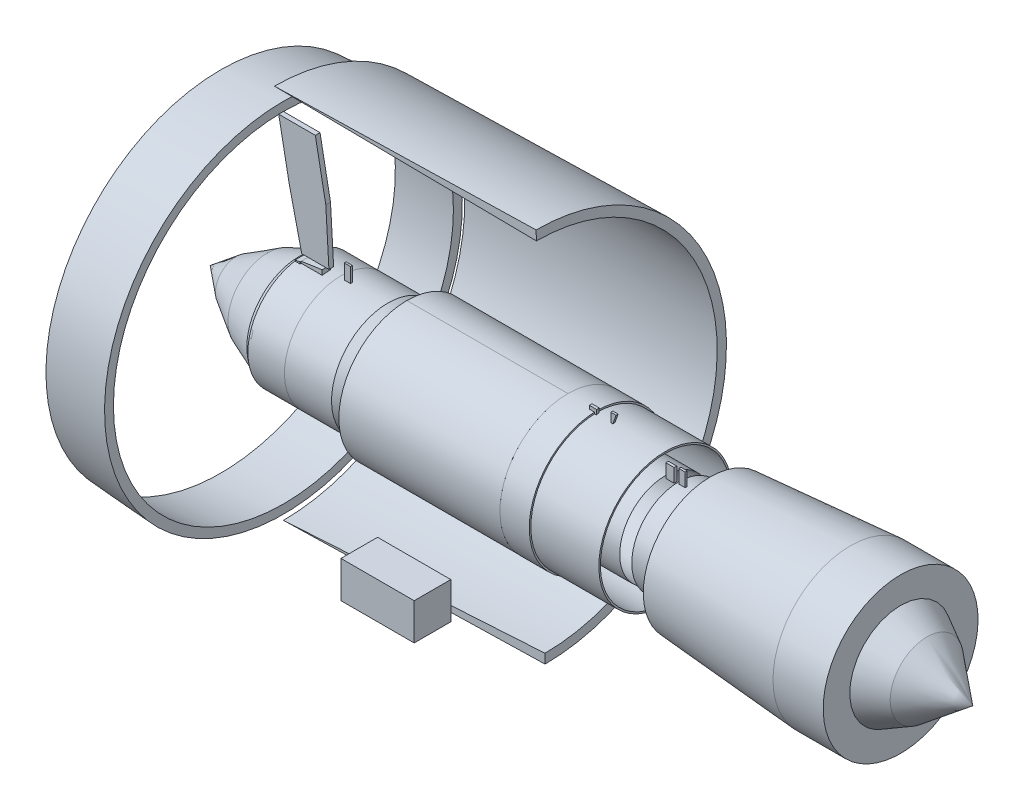
SolidWorks part; units mm, degrees
ref_plane "Front Plane" through (0, 0, 0) normal (0, 0, 1) x (1, 0, 0)
ref_plane "Top Plane" through (0, 0, 0) normal (0, 1, 0) x (1, 0, 0)
ref_plane "Right Plane" through (0, 0, 0) normal (1, 0, 0) x (0, 0, -1)
sketch "Sketch1" plane through (0, 0, 0) normal (0, 0, 1) x (1, 0, 0)
  line L0 (0, 0) -> (1200, 0) construction
  line L1 (0, 0) -> (250, 200)
  line L2 (250, 200) -> (550, 380)
  line L3 (550, 380) -> (850, 500)
  line L4 (850, 500) -> (900, 540)
  line L5 (900, 540) -> (920, 540)
  line L6 (920, 540) -> (920, 460)
  line L7 (920, 460) -> (850, 460)
  line L8 (850, 460) -> (550, 350)
  line L9 (550, 350) -> (250, 170)
  line L10 (250, 170) -> (50, 0)
  line L11 (50, 0) -> (0, 0)
revolve "Revolve1" add sketch "Sketch1" angle 360 about L0
sketch "Sketch2" plane through (0, 0, 0) normal (0, 0, 1) x (1, 0, 0)
  line L0 (0, 0) -> (2000, 0) construction
  line L1 (900, 220) -> (900, 540)
  line L2 (900, 540) -> (900, -540) construction
  line L3 (900, 540) -> (1250, 540)
  line L4 (1250, 540) -> (1250, 220)
  line L5 (1250, 220) -> (900, 220)
revolve "Revolve2" add sketch "Sketch2" angle 360 about L0
sketch "Sketch3" plane through (0, 0, 0) normal (0, 0, 1) x (1, 0, 0)
  line L0 (950, 500) -> (950, 550)
  line L1 (950, 550) -> (1150, 580)
  line L2 (1150, 580) -> (1150, 500)
  line L3 (1150, 500) -> (950, 500)
extrude "Boss-Extrude1" add sketch "Sketch3" along normal blind 80 separate body
sketch "Sketch4" plane through (0, 0, 0) normal (0, 0, 1) x (1, 0, 0)
  line L0 (920, 580) -> (800, 1100)
  line L1 (800, 1100) -> (700, 1625)
  line L2 (700, 1625) -> (1050, 1625)
  line L3 (1050, 1625) -> (1150, 1100)
  line L4 (1150, 1100) -> (1180, 580)
  line L5 (1180, 580) -> (920, 580)
extrude "Boss-Extrude2" add sketch "Sketch4" along normal blind 45 separate body
sketch "Sketch5" plane through (0, 0, 0) normal (0, 0, 1) x (1, 0, 0)
  line L0 (900, 490) -> (900, 540)
  line L1 (900, 540) -> (900, -540) construction
  line L2 (900, 540) -> (950, 550)
  line L3 (950, 550) -> (950, 490)
  line L4 (950, 490) -> (900, 490)
extrude "Boss-Extrude3" add sketch "Sketch5" along normal blind 90 separate body
sketch "Sketch6" plane through (0, 0, 0) normal (0, 0, 1) x (1, 0, 0)
  line L0 (0, 0) -> (2000, 0) construction
  line L1 (100, 1670) -> (700, 1710)
  line L2 (700, 1710) -> (700, 1625)
  line L3 (700, 1625) -> (100, 1670)
revolve "Revolve3" add sketch "Sketch6" angle 360 about L0
sketch "Sketch7" plane through (0, 0, 0) normal (0, 0, 1) x (1, 0, 0)
  line L0 (0, 0) -> (3000, 0) construction
  line L1 (700, 1630) -> (700, 1710)
  line L2 (700, -1710) -> (700, 1710) construction
  line L3 (700, 1710) -> (750, 1750)
  line L4 (750, 1750) -> (700, 1710)
  line L5 (700, 1710) -> (2150, 1710)
  line L6 (2150, 1710) -> (2150, 1750)
  line L7 (2150, 1750) -> (2200, 1750)
  line L8 (2200, 1750) -> (2200, 1630)
  line L9 (2200, 1630) -> (700, 1630)
sketch "Sketch8" plane through (0, 0, 0) normal (0, 0, 1) x (1, 0, 0)
  line L0 (0, 0) -> (3000, 0) construction
  line L1 (1250, 250) -> (1250, 540)
  line L2 (1250, -540) -> (1250, 540) construction
  line L3 (1250, 540) -> (1400, 540)
  line L4 (1400, 540) -> (1550, 540)
  line L5 (1550, 540) -> (1700, 540)
  line L6 (1700, 540) -> (1850, 470)
  line L7 (1850, 470) -> (1850, 250)
  line L8 (1850, 250) -> (1250, 250)
revolve "Revolve5" add sketch "Sketch8" angle 360 about L0
sketch "Sketch9" plane through (0, 0, 0) normal (0, 0, 1) x (1, 0, 0)
  line L0 (1300, 500) -> (1300, 680)
  line L1 (1300, 680) -> (1360, 680)
  line L2 (1360, 680) -> (1360, 500)
  line L3 (1360, 500) -> (1300, 500)
extrude "Boss-Extrude5" add sketch "Sketch9" along normal blind 18 separate body
sketch "Sketch10" plane through (0, 0, 0) normal (0, 0, 1) x (1, 0, 0)
  line L0 (0, 0) -> (3000, 0) construction
  line L1 (1500, 500) -> (1500, 700)
  line L2 (1500, 700) -> (1500, 500)
  line L3 (1500, 500) -> (1450, 500)
sketch "Sketch11" plane through (0, 0, 0) normal (0, 0, 1) x (1, 0, 0)
  line L0 (0, 0) -> (4000, 0) construction
  line L1 (1900, 280) -> (1900, 460)
  line L2 (1900, 460) -> (3400, 460)
  line L3 (3400, 460) -> (3400, 280)
  line L4 (3400, 280) -> (1900, 280)
revolve "Revolve7" add sketch "Sketch11" angle 360 about L0
sketch "Sketch12" plane through (0, 0, 0) normal (0, 0, 1) x (1, 0, 0)
  line L0 (2000, 450) -> (2000, 580)
  line L1 (2000, 580) -> (2050, 580)
  line L2 (2050, 580) -> (2050, 450)
  line L3 (2050, 450) -> (2000, 450)
extrude "Boss-Extrude6" add sketch "Sketch12" along normal blind 15 separate body
sketch "Sketch13" plane through (0, 0, 0) normal (0, 0, 1) x (1, 0, 0)
  line L0 (0, 0) -> (4000, 0) construction
  line L1 (1880, 580) -> (1880, 650)
  line L2 (1880, 650) -> (3420, 650)
  line L3 (3420, 650) -> (3420, 580)
  line L4 (3420, 580) -> (1880, 580)
revolve "Revolve8" add sketch "Sketch13" angle 180 about L0
sketch "Sketch14" plane through (0, 0, 0) normal (0, 0, 1) x (1, 0, 0)
  line L0 (0, 0) -> (4000, 0) construction
  line L1 (1880, -580) -> (1880, -650)
  line L2 (1880, -650) -> (3420, -650)
  line L3 (3420, -650) -> (3420, 650) construction
  line L4 (3420, -650) -> (3420, -580)
  line L5 (3420, -580) -> (1880, -580)
revolve "Revolve9" add sketch "Sketch14" angle 180 about L0
sketch "Sketch15" plane through (0, 0, 0) normal (0, 0, 1) x (1, 0, 0)
  line L0 (0, 0) -> (5000, 0) construction
  line L1 (3420, 350) -> (3420, 650)
  line L2 (3420, -650) -> (3420, 650) construction
  line L3 (3420, 650) -> (3700, 650)
  line L4 (3700, 650) -> (3700, 350)
  line L5 (3700, 350) -> (3420, 350)
revolve "Revolve10" add sketch "Sketch15" angle 360 about L0
sketch "Sketch16" plane through (0, 0, 0) normal (0, 0, 1) x (1, 0, 0)
  line L0 (0, 0) -> (5000, 0) construction
  line L1 (3700, 620) -> (3700, 635)
  line L2 (3700, 635) -> (4350, 635)
  line L3 (4350, 635) -> (4350, 620)
  line L4 (4350, 620) -> (3700, 620)
revolve "Revolve11" add sketch "Sketch16" angle 360 about L0
sketch "Sketch17" plane through (0, 0, 0) normal (0, 0, 1) x (1, 0, 0)
  line L0 (0, 0) -> (5000, 0) construction
  line L1 (3700, 420) -> (3700, 435)
  line L2 (3700, -650) -> (3700, 650) construction
  line L3 (3700, 435) -> (4350, 435)
  line L4 (4350, -635) -> (4350, 635) construction
  line L5 (4350, 435) -> (3700, 420)
revolve "Revolve12" add sketch "Sketch17" angle 360 about L0
sketch "Sketch18" plane through (0, 0, 0) normal (0, 0, 1) x (1, 0, 0)
  line L0 (3650, 500) -> (3650, 680)
  line L1 (3650, 680) -> (3720, 680)
  line L2 (3720, 680) -> (3700, 500)
  line L3 (3700, 635) -> (3700, -635) construction
  line L4 (3700, 500) -> (3650, 500)
extrude "Boss-Extrude7" add sketch "Sketch18" along normal blind 25 separate body
sketch "Sketch19" plane through (0, 0, 0) normal (0, 0, 1) x (1, 0, 0)
  line L0 (3850, 580) -> (3850, 720)
  line L1 (3850, 720) -> (3900, 720)
  line L2 (3900, 720) -> (3850, 580)
extrude "Boss-Extrude8" add sketch "Sketch19" along normal blind 20 separate body
sketch "Sketch20" plane through (0, 0, 0) normal (0, 0, 1) x (1, 0, 0)
  line L0 (4380, 440) -> (4380, 570)
  line L1 (4380, 570) -> (4460, 570)
  line L2 (4460, 570) -> (4460, 440)
  line L3 (4460, 440) -> (4380, 440)
extrude "Boss-Extrude9" add sketch "Sketch20" along normal blind 25 separate body
sketch "Sketch21" plane through (0, 0, 0) normal (0, 0, 1) x (1, 0, 0)
  line L0 (0, 0) -> (5500, 0) construction
  line L1 (4480, 250) -> (4480, 450)
  line L2 (4480, 450) -> (4750, 450)
  line L3 (4750, 450) -> (4750, 250)
  line L4 (4750, 250) -> (4480, 250)
revolve "Revolve13" add sketch "Sketch21" angle 360 about L0
sketch "Sketch22" plane through (0, 0, 0) normal (0, 0, 1) x (1, 0, 0)
  line L0 (4500, 450) -> (4500, 580)
  line L1 (4500, 580) -> (4560, 580)
  line L2 (4560, 580) -> (4560, 450)
  line L3 (4560, 450) -> (4500, 450)
extrude "Boss-Extrude10" add sketch "Sketch22" along normal blind 20 separate body
sketch "Sketch23" plane through (0, 0, 0) normal (0, 0, 1) x (1, 0, 0)
  line L0 (0, 0) -> (7000, 0) construction
  line L1 (4800, 250) -> (4800, 460)
  line L2 (4800, 460) -> (6100, 550)
  line L3 (6100, 550) -> (6100, 250)
  line L4 (6100, 250) -> (4800, 250)
revolve "Revolve14" add sketch "Sketch23" angle 360 about L0
sketch "Sketch24" plane through (0, 0, 0) normal (0, 0, 1) x (1, 0, 0)
  line L0 (5200, 490) -> (5200, 660)
  line L1 (5200, 660) -> (5270, 660)
  line L2 (5270, 660) -> (5270, 490)
  line L3 (5270, 490) -> (5200, 490)
extrude "Boss-Extrude11" add sketch "Sketch24" along normal blind 20 separate body
sketch "Sketch25" plane through (0, 0, 0) normal (0, 0, 1) x (1, 0, 0)
  line L0 (0, 0) -> (7000, 0) construction
  line L1 (4780, 580) -> (4780, 640)
  line L2 (4780, 640) -> (6120, 740)
  line L3 (6120, 740) -> (6120, 670)
  line L4 (6120, 670) -> (4780, 580)
revolve "Revolve15" add sketch "Sketch25" angle 360 about L0
sketch "Sketch26" plane through (0, 0, 0) normal (0, 0, 1) x (1, 0, 0)
  line L0 (0, 0) -> (8000, 0) construction
  line L1 (6120, 300) -> (6120, 740)
  line L2 (6120, -740) -> (6120, 740) construction
  line L3 (6120, 740) -> (6600, 740)
  line L4 (6600, 740) -> (6600, 300)
  line L5 (6600, 300) -> (6120, 300)
revolve "Revolve16" add sketch "Sketch26" angle 360 about L0
sketch "Sketch27" plane through (0, 0, 0) normal (0, 0, 1) x (1, 0, 0)
  line L0 (0, 0) -> (8000, 0) construction
  line L1 (6300, 350) -> (6300, 650)
  line L2 (6300, 650) -> (6850, 350)
  line L3 (6850, 350) -> (7290, 0)
  line L4 (7290, 0) -> (6300, 0)
  line L5 (6300, 0) -> (6300, 350)
revolve "Revolve17" add sketch "Sketch27" angle 360 about L0
sketch "Sketch28" plane through (0, 0, 0) normal (0, 0, 1) x (1, 0, 0)
  line L0 (0, 0) -> (8000, 0) construction
  line L1 (900, 0) -> (900, 120)
  line L2 (900, 540) -> (900, -540) construction
  line L3 (900, 120) -> (6200, 120)
  line L4 (6200, 120) -> (6200, 80)
  line L5 (6200, 80) -> (900, 120)
sketch "Sketch29" plane through (0, 0, 0) normal (0, 0, 1) x (1, 0, 0)
  line L0 (0, 0) -> (6000.6151, 81.5048) construction
  line L1 (6200, 80) -> (900, 120) construction
  line L2 (1900, 81.5048) -> (1900, 120)
  line L3 (900, 120) -> (6200, 120) construction
  line L4 (1900, 120) -> (4700, 120)
  line L5 (4700, 120) -> (4700, 140)
  line L6 (4700, 140) -> (1900, 120)
sketch "Sketch30" plane through (0, 0, 0) normal (0, 0, 1) x (1, 0, 0)
  line L0 (0, 0) -> (2000, 0) construction
  line L1 (0, 0) -> (3000, 0) construction
  line L2 (1100, 120) -> (1180, 120)
  line L3 (900, 120) -> (6200, 120) construction
  line L4 (1180, 120) -> (1100, 120)
sketch "Sketch31" plane through (0, 0, 0) normal (0, 0, 1) x (1, 0, 0)
  line L0 (0, 0) -> (2000, 0) construction
sketch "Sketch32" plane through (0, 0, 0) normal (0, 0, 1) x (1, 0, 0)
  line L0 (1600, -1450) -> (1600, -1800)
  line L1 (1600, -1800) -> (2300, -1800)
  line L2 (2300, -1800) -> (2300, -1450)
  line L3 (2300, -1450) -> (1600, -1450)
extrude "Boss-Extrude12" add sketch "Sketch32" along normal blind 350 separate body
sketch "Sketch33" plane through (0, 0, 0) normal (0, 0, 1) x (1, 0, 0)
  line L0 (0, 0) -> (4000.729, 96.5983) construction
  line L1 (6200, 80) -> (900, 120) construction
  line L2 (700, 1720) -> (700, 1710)
  line L3 (700, 1720) -> (3200, 1720)
  line L4 (3200, 1720) -> (3200, 1610)
  line L5 (3200, 1610) -> (700, 1720)
sketch "Sketch34" plane through (0, 0, 0) normal (0, 0, 1) x (1, 0, 0)
  line L0 (0, 0) -> (4000.729, 96.5983) construction
  line L1 (700, -1760) -> (3201.1978, -1699.6082)
  line L2 (3201.1978, -1699.6082) -> (3200, -1610)
  line L3 (3200, -1610) -> (700, -1760)
revolve "Revolve23" add sketch "Sketch34" angle 180 about L0
sketch "Sketch35" plane through (0, 0, 0) normal (0, 0, 1) x (1, 0, 0)
  line L0 (0, 0) -> (6000.6151, 81.5048) construction
  line L1 (3200, 1610) -> (3200, 1720)
  line L2 (3200, 1610) -> (5500, 1300)
  line L3 (5500, 1300) -> (5500, 1250)
  line L4 (5500, 1250) -> (3200, 1610)
